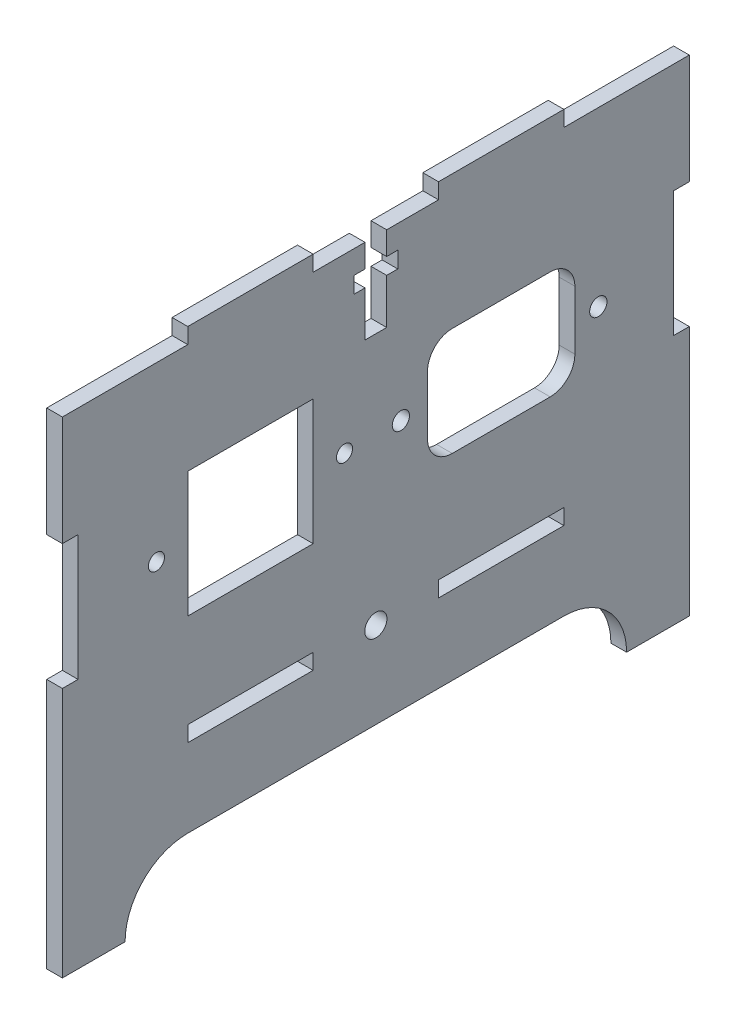
SolidWorks part; units mm, degrees
ref_plane "Front Plane" through (0, 0, 0) normal (0, 0, 1) x (1, 0, 0)
ref_plane "Top Plane" through (0, 0, 0) normal (0, 1, 0) x (1, 0, 0)
ref_plane "Right Plane" through (0, 0, 0) normal (1, 0, 0) x (0, 0, -1)
sketch "Sketch1" plane through (0, 0, 0) normal (1, 0, 0) x (0, 0, -1)
  line L1 (-63.5, 50.8) -> (63.5, 50.8)
  line L2 (-63.5, 50.8) -> (-63.5, -50.8)
  line L3 (-63.5, -50.8) -> (63.5, -50.8)
  line L4 (63.5, 50.8) -> (63.5, -50.8)
  line L5 (-63.5, 50.8) -> (63.5, -50.8) construction
  line L6 (-63.5, -50.8) -> (63.5, 50.8) construction
  point P0 (0, 0)
  dimension "D1" = 127
  dimension "D2" = 101.6
extrude "Boss-Extrude1" add sketch "Sketch1" along normal blind 3.175
sketch "Sketch2" plane through (3.175, 0, 0) normal (1, 0, 0) x (0, 0, -1)
  line L1 (-63.5, 50.8) -> (-38.1, 50.8)
  line L2 (-63.5, 50.8) -> (-63.5, 47.625)
  line L3 (-63.5, 47.625) -> (-38.1, 47.625)
  line L4 (-38.1, 50.8) -> (-38.1, 47.625)
  dimension "D1" = 25.4
  dimension "D2" = 3.175
extrude "Cut-Extrude1" cut sketch "Sketch2" against normal blind 6.35
pattern_linear "LPattern1" count 3 spacing 50.8 along (0, 0, -1) of "Cut-Extrude1"
sketch "Sketch5" plane through (3.175, 0, 0) normal (1, 0, 0) x (0, 0, -1)
  line L0 (-38.1, -50.8) -> (38.1, -50.8) construction
  line L1 (-63.5, -50.8) -> (63.5, -50.8) construction
  line L2 (-38.1, -38.1) -> (38.1, -38.1)
  line L3 (-38.1, -63.5) -> (38.1, -63.5)
  arc A0 (-38.1, -38.1) -> (-38.1, -63.5) centre (-38.1, -50.8) ccw
  arc A1 (38.1, -63.5) -> (38.1, -38.1) centre (38.1, -50.8) ccw
  point P4 (0, -50.8)
  dimension "D2" = 12.7
  dimension "D1" = 76.2
extrude "Cut-Extrude4" cut sketch "Sketch5" against normal blind 6.35
sketch "Sketch8" plane through (3.175, 0, 0) normal (1, 0, 0) x (0, 0, -1)
  line L0 (63.5, -50.8) -> (63.5, 47.625) construction
  line L1 (63.5, 25.4) -> (60.325, 25.4)
  line L2 (63.5, 25.4) -> (63.5, 0)
  line L3 (63.5, 0) -> (60.325, 0)
  line L4 (60.325, 25.4) -> (60.325, 0)
  line L5 (38.1, 50.8) -> (12.7, 50.8) construction
  dimension "D1" = 25.4
  dimension "D2" = 25.4
  dimension "D3" = 3.175
extrude "Cut-Extrude6" cut sketch "Sketch8" against normal blind 6.35
ref_plane "Plane1" through (0, 0, 0) normal (0, 0, 1) x (1, 0, 0)
sketch "Sketch9" plane through (0, 0, 0) normal (-1, 0, 0) x (0, 0, 1)
  line L0 (-63.5, -50.8) -> (-63.5, 0) construction
  line L1 (-38.1, -19.05) -> (-12.7, -19.05)
  line L2 (-38.1, -19.05) -> (-38.1, -22.225)
  line L3 (-38.1, -22.225) -> (-12.7, -22.225)
  line L4 (-12.7, -19.05) -> (-12.7, -22.225)
  line L5 (-38.1, 50.8) -> (-12.7, 50.8) construction
  point P6 (-25.4, 50.8)
  dimension "D1" = 25.4
  dimension "D2" = 3.175
  dimension "D3" = 25.4
  dimension "D4" = 69.85
extrude "Cut-Extrude7" cut sketch "Sketch9" against normal blind 6.35
pattern_linear "LPattern6" count 2 spacing 50.8 along (0, 0, 1) of "Cut-Extrude7"
sketch "Sketch16" plane through (0, 0, 0) normal (-1, 0, 0) x (0, 0, 1)
  line L0 (12.7, 47.625) -> (-12.7, 47.625) construction
  line L1 (-2.1971, 47.625) -> (2.1971, 47.625)
  line L2 (-2.1971, 47.625) -> (-2.1971, 30.48)
  line L3 (-2.1971, 30.48) -> (2.1971, 30.48)
  line L4 (2.1971, 47.625) -> (2.1971, 30.48)
  line L5 (-12.7, 47.625) -> (-12.7, 50.8) construction
  line L7 (-4.445, 42.926) -> (4.445, 42.926)
  line L8 (-4.445, 42.926) -> (-4.445, 39.624)
  line L9 (-4.445, 39.624) -> (4.445, 39.624)
  line L10 (4.445, 42.926) -> (4.445, 39.624)
  point P6 (0, 30.48)
  point P13 (0, 42.926)
  point P14 (4.445, 41.275)
  dimension "D1" = 4.3942
  dimension "D2" = 17.145
  dimension "D3" = 12.7
  dimension "D4" = 3.302
  dimension "D5" = 8.89
  dimension "D6" = 12.7
  dimension "D7" = 6.35
extrude "Cut-Extrude14" cut sketch "Sketch16" against normal blind 6.35 contours L7 L10 L9 L8 | L1 L4 L3 L2
hole_wizard "#8 Clearance Hole1" positions "Sketch18" profile "Sketch17" hole size "#8" standard "ANSI Inch"
sketch "Sketch18" plane through (0, 0, 0) normal (-1, 0, 0) x (0, 0, 1)
  line L3 (-12.7, -22.225) -> (-12.7, -19.05) construction
  line L4 (38.1, -19.05) -> (12.7, -19.05) construction
  point P0 (0, -20.6375)
  point P16 (-12.7, -20.6375)
  dimension "D1" = 12.7
  dimension "D2" = 1.5875
sketch "Sketch17" plane through (0, -20.6375, 0) normal (0, 1, 0) x (0, 0, 1)
  line L0 (0, 0) -> (0, 11.5107)
  line L1 (0, 11.5107) -> (2.2479, 10.16)
  line L2 (2.2479, 10.16) -> (2.2479, 0)
  line L5 (2.2479, 0) -> (0, 0)
  line L10 (0, 11.5107) -> (-2.2479, 10.16) construction
  line L11 (0, -6.35) -> (0, 107.95) construction
  dimension "Hole Dia." = 4.4958
  dimension "Hole Depth" = 10.16
  dimension "Drill Angle" = 118
sketch "Sketch19" plane through (0, 0, 0) normal (-1, 0, 0) x (0, 0, 1)
  line L0 (-49.53, 42.545) -> (-11.43, 42.545) construction
  line L1 (-49.53, 43.815) -> (-11.43, 43.815)
  line L2 (-49.53, 41.275) -> (-11.43, 41.275)
  line L3 (-38.1, 50.8) -> (-38.1, 47.625) construction
  line L4 (-2.1971, 47.625) -> (-12.7, 47.625) construction
  arc A0 (-49.53, 43.815) -> (-49.53, 41.275) centre (-49.53, 42.545) ccw
  arc A1 (-11.43, 41.275) -> (-11.43, 43.815) centre (-11.43, 42.545) ccw
  point P2 (-30.48, 42.545)
  point P7 (-30.48, 43.815)
  dimension "D2" = 1.27
  dimension "D1" = 38.1
  dimension "D3" = 7.62
  dimension "D4" = 3.81
extrude "Cut-Extrude15" [suppressed] cut sketch "Sketch19" against normal blind 6.35
mirror "Mirror2" [suppressed] about plane through (0, 0, 0) normal (0, 0, 1)
pattern_linear "LPattern7" [suppressed] count 5 spacing 5.08
sketch "Sketch20" plane through (0, 0, 0) normal (-1, 0, 0) x (0, 0, 1)
  line L0 (-38.1, 50.8) -> (-12.7, 50.8) construction
  line L1 (-35.3225, 23.6601) -> (-15.4775, 23.6601)
  line L2 (-40.3225, 18.6601) -> (-40.3225, 6.7399)
  line L3 (-35.3225, 1.7399) -> (-15.4775, 1.7399)
  line L4 (-10.4775, 18.6601) -> (-10.4775, 6.7399)
  line L5 (-63.5, -50.8) -> (-63.5, 0) construction
  circle A0 centre (-45.0725, 12.7) radius 1.75
  circle A1 centre (-5.0725, 12.7) radius 1.75
  arc A2 (-40.3225, 6.7399) -> (-35.3225, 1.7399) centre (-35.3225, 6.7399) ccw
  arc A3 (-15.4775, 23.6601) -> (-10.4775, 18.6601) centre (-15.4775, 18.6601) cw
  arc A4 (-15.4775, 1.7399) -> (-10.4775, 6.7399) centre (-15.4775, 6.7399) ccw
  arc A5 (-40.3225, 18.6601) -> (-35.3225, 23.6601) centre (-35.3225, 18.6601) cw
  point P8 (-25.4, 23.6601)
  point P13 (-40.3225, 12.7)
  point P18 (-10.4775, 23.6601)
  point P21 (-10.4775, 1.7399)
  point P24 (-40.3225, 23.6601)
  dimension "D1" = 3.5
  dimension "D2" = 3.5
  dimension "D10" = 5
  dimension "D11" = 5
  dimension "D12" = 5
  dimension "D13" = 5
  dimension "D3" = 40
  dimension "D4" = 29.845
  dimension "D5" = 21.9202
  dimension "D6" = 38.1
  dimension "D7" = 38.1
extrude "Cut-Extrude16" cut sketch "Sketch20" against normal blind 7.62
sketch "Sketch25" plane through (0, 0, 0) normal (-1, 0, 0) x (0, 0, 1)
  line L0 (12.7, -19.05) -> (12.7, -22.225) construction
  line L1 (12.7, 0) -> (38.1, 0)
  line L2 (12.7, 0) -> (12.7, 25.4)
  line L3 (12.7, 25.4) -> (38.1, 25.4)
  line L4 (38.1, 0) -> (38.1, 25.4)
  line L6 (12.7, 50.8) -> (38.1, 50.8) construction
  point P6 (12.7, 12.7)
  dimension "D1" = 25.4
  dimension "D2" = 25.4
  dimension "D3" = 38.1
extrude "Cut-Extrude20" cut sketch "Sketch25" against normal blind 7.62
mirror "Mirror3" about plane through (0, 0, 0) normal (0, 0, 1) of "Cut-Extrude6"
hole_wizard "#4 Clearance Hole1" positions "Sketch27" profile "Sketch26" hole size "#4" standard "ANSI Inch"
sketch "Sketch27" plane through (3.175, 0, 0) normal (1, 0, 0) x (0, 0, -1)
  line L0 (-38.1, 25.4) -> (-38.1, 0) construction
  line L1 (-12.7, 0) -> (-12.7, 25.4) construction
  point P0 (-44.45, 12.7)
  point P2 (-6.35, 12.7)
  point P11 (-38.1, 12.7)
  point P12 (-12.7, 12.7)
  dimension "D1" = 6.35
  dimension "D2" = 6.35
sketch "Sketch26" plane through (3.175, 12.7, 44.45) normal (0, 1, 0) x (0, 0, -1)
  line L0 (0, 0) -> (0, 11.1406)
  line L1 (0, 11.1406) -> (1.6319, 10.16)
  line L2 (1.6319, 10.16) -> (1.6319, 0)
  line L5 (1.6319, 0) -> (0, 0)
  line L10 (0, 11.1406) -> (-1.6319, 10.16) construction
  line L11 (0, -6.35) -> (0, 107.95) construction
  dimension "Hole Dia." = 3.2639
  dimension "Hole Depth" = 10.16
  dimension "Drill Angle" = 118
